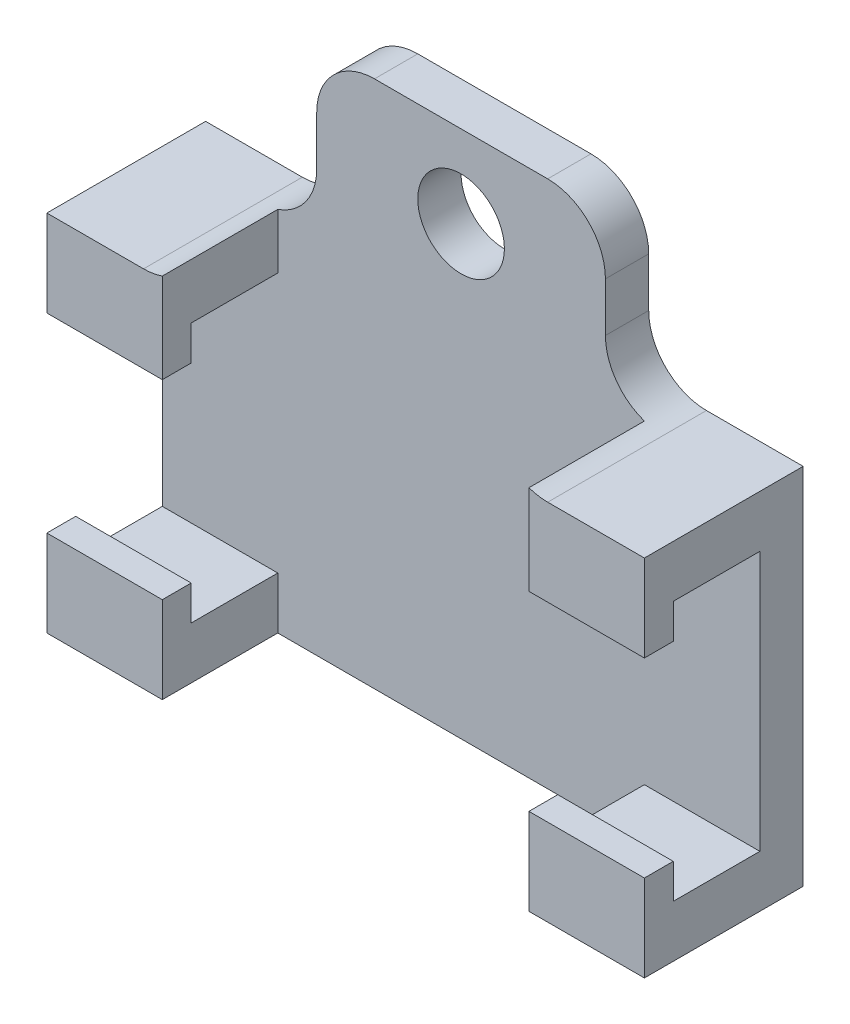
SolidWorks part; units mm, degrees
ref_plane "Front" through (0, 0, 0) normal (0, 0, 1) x (1, 0, 0)
ref_plane "Top" through (0, 0, 0) normal (0, 1, 0) x (1, 0, 0)
ref_plane "Right" through (0, 0, 0) normal (1, 0, 0) x (0, 0, -1)
sketch "Sketch1" plane through (0, 0, 0) normal (0, 1, 0) x (1, 0, 0)
  line L1 (0, 0) -> (20.7, 0)
  line L2 (0, 0) -> (0, 24)
  line L3 (0, 24) -> (20.7, 24)
  line L4 (20.7, 0) -> (20.7, 24)
  dimension "D1" = 20.7
  dimension "D2" = 24
extrude "Boss-Extrude1" add sketch "Sketch1" along normal blind 1.5
sketch "Sketch2" plane through (0, 1.5, 0) normal (0, 1, 0) x (1, 0, 0)
  line L0 (0, 24) -> (0, 0) construction
  line L1 (0, 15.3) -> (20.7, 15.3)
  line L2 (0, 15.3) -> (0, 18.3)
  line L3 (0, 18.3) -> (20.7, 18.3)
  line L4 (20.7, 15.3) -> (20.7, 18.3)
  line L5 (20.7, 0) -> (20.7, 24) construction
  line L7 (0, 8.7) -> (20.7, 8.7)
  line L8 (0, 8.7) -> (0, 5.7)
  line L9 (0, 5.7) -> (20.7, 5.7)
  line L10 (20.7, 8.7) -> (20.7, 5.7)
  line L11 (10.35, 8.7) -> (10.35, 15.3) construction
  point P14 (0, 12)
  point P15 (10.35, 12)
  dimension "D2" = 3
  dimension "D3" = 3
  dimension "D1" = 6.6
extrude "Boss-Extrude2" add sketch "Sketch2" along normal blind 4
sketch "Sketch3" plane through (0, 0, -15.3) normal (0, 0, 1) x (1, 0, 0)
  line L0 (20.7, 5.5) -> (20.7, 1.5) construction
  line L1 (0, 1.5) -> (20.7, 1.5)
  line L2 (0, 1.5) -> (0, 4.5)
  line L3 (0, 4.5) -> (20.7, 4.5)
  line L4 (20.7, 1.5) -> (20.7, 4.5)
  dimension "D1" = 3
extrude "Cut-Extrude1" cut sketch "Sketch3" against normal blind 1.2
sketch "Sketch4" plane through (0, 0, -8.7) normal (0, 0, -1) x (-1, 0, 0)
  line L0 (0, 5.5) -> (0, 1.5) construction
  line L1 (-20.7, 1.5) -> (0, 1.5)
  line L2 (-20.7, 1.5) -> (-20.7, 4.5)
  line L3 (-20.7, 4.5) -> (0, 4.5)
  line L4 (0, 1.5) -> (0, 4.5)
  dimension "D1" = 3
extrude "Cut-Extrude2" cut sketch "Sketch4" against normal blind 1.2
sketch "Sketch5" plane through (0, 1.5, 0) normal (0, 1, 0) x (1, 0, 0)
  line L0 (0, 24) -> (0, 18.3) construction
  line L1 (20.7, 24) -> (0, 24) construction
  line L2 (0, 5.7) -> (0, 0) construction
  circle A0 centre (10.35, 21.15) radius 1.5
  circle A1 centre (10.35, 2.85) radius 1.5
  point P6 (0, 21.15)
  point P9 (10.35, 24)
  point P12 (0, 2.85)
  dimension "D1" = 3
  dimension "D2" = 3
extrude "Cut-Extrude3" cut sketch "Sketch5" against normal through all
sketch "Sketch6" plane through (0, 0, 0) normal (0, -1, 0) x (1, 0, 0)
  line L0 (10.35, -21.15) -> (10.35, -5.7)
  line L1 (0, -5.7) -> (20.7, -5.7) construction
sketch "Sketch7" plane through (0, 0, 0) normal (0, 1, 0) x (1, 0, 0)
  line L1 (0, 5.7) -> (20.7, 5.7)
  line L2 (0, 5.7) -> (0, 0)
  line L3 (0, 0) -> (20.7, 0)
  line L4 (20.7, 5.7) -> (20.7, 0)
extrude "Cut-Extrude4" cut sketch "Sketch7" along normal through all
sketch "Sketch8" plane through (0, 0, -5.7) normal (0, 0, 1) x (1, 0, 0)
  line L0 (0, 5.5) -> (20.7, 5.5) construction
  line L1 (4, 5.5) -> (16.7, 5.5)
  line L2 (4, 5.5) -> (4, 1.5)
  line L3 (4, 1.5) -> (16.7, 1.5)
  line L4 (16.7, 5.5) -> (16.7, 1.5)
  line L5 (0, 1.5) -> (20.7, 1.5) construction
  line L6 (0, 1.5) -> (4, 1.5) construction
  line L16 (0, 5.5) -> (0, 0) construction
  point P8 (10.35, 5.5)
  point P9 (10.35, 5.5)
  dimension "D1" = 4
extrude "Cut-Extrude5" cut sketch "Sketch8" against normal through all
sketch "Sketch9" plane through (0, 1.5, 0) normal (0, 1, 0) x (1, 0, 0)
  line L0 (4, 18.3) -> (0, 18.3) construction
  line L1 (0, 24) -> (5.35, 24)
  line L2 (0, 24) -> (0, 18.3)
  line L3 (0, 18.3) -> (5.35, 18.3)
  line L4 (5.35, 24) -> (5.35, 18.3)
  line L5 (10.35, 24) -> (10.35, 5.7) construction
  line L6 (20.7, 24) -> (0, 24) construction
  line L7 (4, 5.7) -> (16.7, 5.7) construction
  line L8 (15.35, 24) -> (15.35, 18.3)
  line L9 (20.7, 18.3) -> (15.35, 18.3)
  line L10 (20.7, 24) -> (20.7, 18.3)
  line L11 (20.7, 24) -> (15.35, 24)
  dimension "D1" = 5
extrude "Cut-Extrude6" cut sketch "Sketch9" against normal through all
fillet "Fillet1" radius 2 4 edges at (5.35, 0.75, -18.3) (5.35, 0.75, -24) (15.35, 0.75, -24) (15.35, 0.75, -18.3)
move or copy body "Body-Move/Copy1" bodies to move or copy 109 copy no rotation origin (0, 2.75, -20.7) rotation axis (1, 0, 0) rotation angle 90
equation "\"Board Length\"= 9'The dimension of the board parallel with the clips"
equation "\"Board Width\" = 20.7'The dimension of the board perpendicular to the clips"
equation "\"D1@Sketch1\"=\"Board Width\""
equation "\"Board Slot Length\"= \"Board Length\" - 2 * \"Overhang Cut\""
equation "\"Overhang Cut\"= 1.2"
equation "\"D1@Cut-Extrude1\"=\"Overhang Cut\""
equation "\"D1@Sketch2\"=\"Board Slot Length\""
equation "\"Mount Length\"= \"Board Length\" + 7.5 * 2"
equation "\"D2@Sketch1\"=\"Mount Length\""
